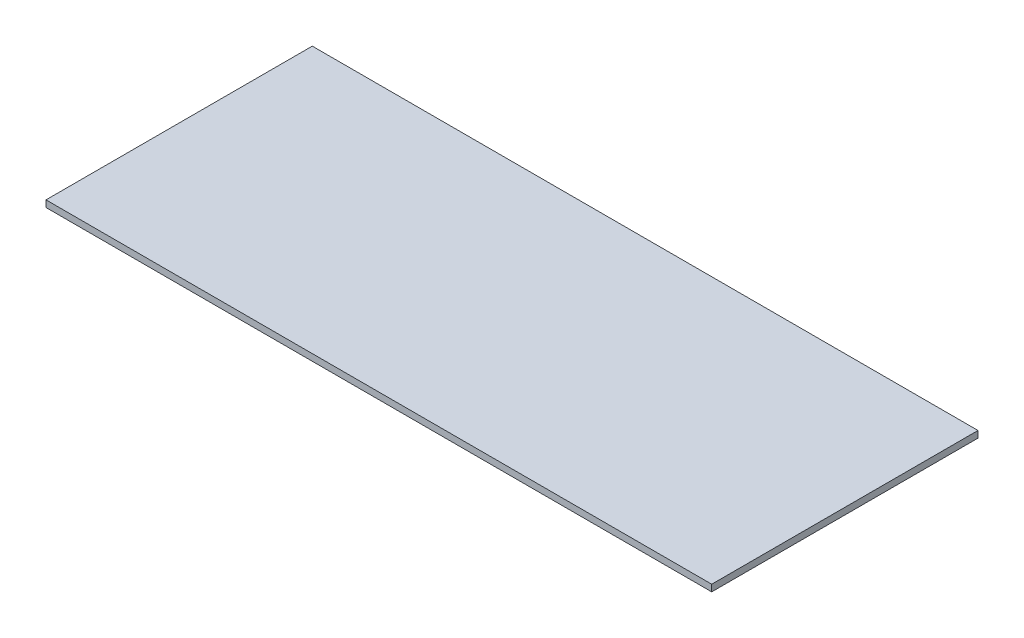
SolidWorks part; units mm, degrees
material "Natural Rubber"
ref_plane "Front Plane" through (0, 0, 0) normal (0, 0, 1) x (1, 0, 0)
ref_plane "Top Plane" through (0, 0, 0) normal (0, 1, 0) x (1, 0, 0)
ref_plane "Right Plane" through (0, 0, 0) normal (1, 0, 0) x (0, 0, -1)
sketch "Sketch1" plane through (0, 0, 0) normal (0, 1, 0) x (1, 0, 0)
  line L1 (-2500, 1000) -> (2500, 1000)
  line L2 (-2500, 1000) -> (-2500, -1000)
  line L3 (-2500, -1000) -> (2500, -1000)
  line L4 (2500, 1000) -> (2500, -1000)
  line L5 (-2500, 1000) -> (2500, -1000) construction
  line L6 (-2500, -1000) -> (2500, 1000) construction
  point P0 (0, 0)
  dimension "D1" = 5000
  dimension "D2" = 2000
extrude "Boss-Extrude1" add sketch "Sketch1" along normal blind 50
